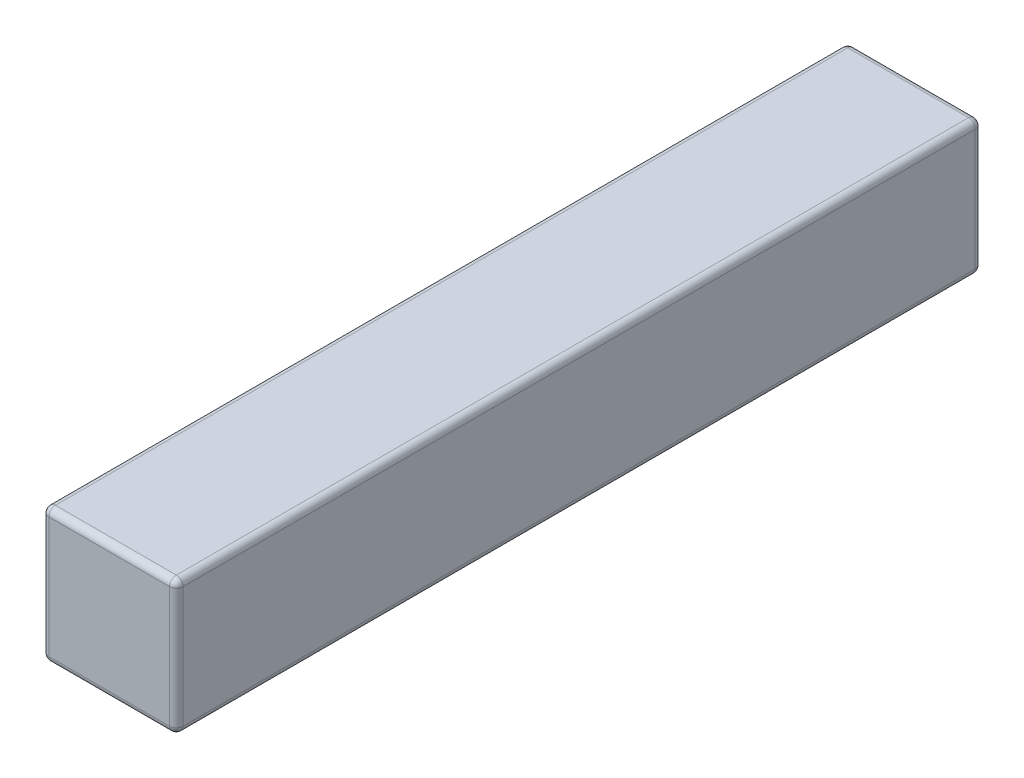
SolidWorks part; units mm, degrees
ref_plane "Front Plane" through (0, 0, 0) normal (0, 0, 1) x (1, 0, 0)
ref_plane "Top Plane" through (0, 0, 0) normal (0, 1, 0) x (1, 0, 0)
ref_plane "Right Plane" through (0, 0, 0) normal (1, 0, 0) x (0, 0, -1)
sketch "Sketch2" plane through (0, 0, 0) normal (0, 0, 1) x (1, 0, 0)
  line L1 (0, 0) -> (50.8, 0)
  line L2 (0, 0) -> (0, 50.8)
  line L3 (0, 50.8) -> (50.8, 50.8)
  line L4 (50.8, 0) -> (50.8, 50.8)
  dimension "D1" = 50.8
  dimension "D2" = 50.8
extrude "Boss-Extrude1" add sketch "Sketch2" along normal blind 304.8
fillet "Fillet1" radius 2.54 12 edges at (50.8, 25.4, 0) (25.4, 0, 0) (0, 25.4, 0) (25.4, 50.8, 0) (0, 0, 152.4) (50.8, 0, 152.4) (25.4, 0, 304.8) (0, 25.4, 304.8) (50.8, 25.4, 304.8) (25.4, 50.8, 304.8) (50.8, 50.8, 152.4) (0, 50.8, 152.4)
sketch "Sketch3" plane through (0, 0, 0) normal (0, 0, -1) x (-1, 0, 0)
  text T0 "<b>+  -</b>" font "Century Gothic" height in points 72
extrude "Boss-Extrude2" add sketch "Sketch3" along normal blind 1.27
